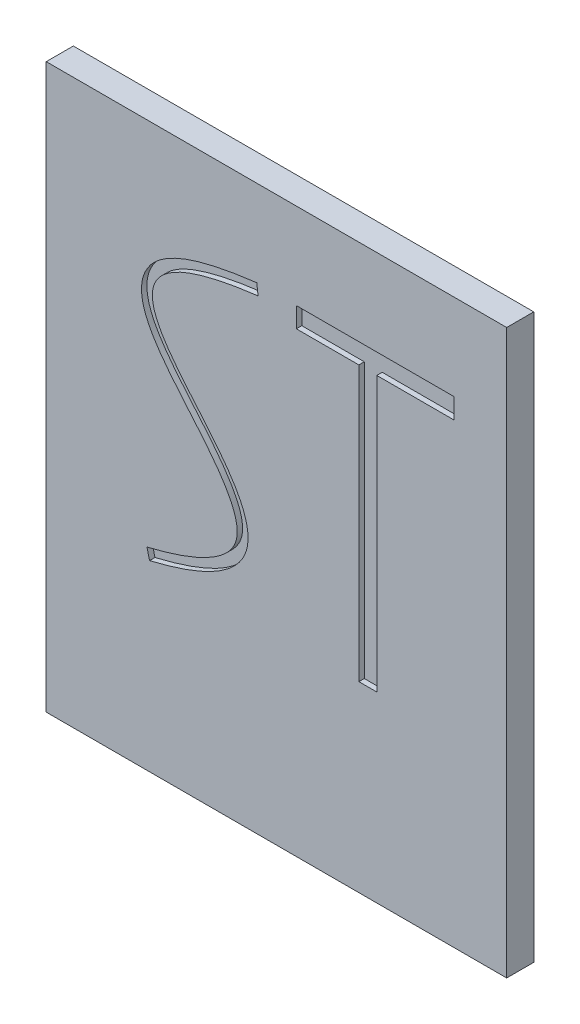
SolidWorks part; units mm, degrees
ref_plane "Front Plane" through (0, 0, 0) normal (0, 0, 1) x (1, 0, 0)
ref_plane "Top Plane" through (0, 0, 0) normal (0, 1, 0) x (1, 0, 0)
ref_plane "Right Plane" through (0, 0, 0) normal (1, 0, 0) x (0, 0, -1)
sketch "Esquisse1" plane through (0, 0, 0) normal (0, 0, 1) x (1, 0, 0)
  line L1 (42.5, 52) -> (-42.5, 52)
  line L2 (42.5, 52) -> (42.5, -52)
  line L3 (42.5, -52) -> (-42.5, -52)
  line L4 (-42.5, 52) -> (-42.5, -52)
  line L5 (42.5, 52) -> (-42.5, -52) construction
  line L6 (42.5, -52) -> (-42.5, 52) construction
  point P0 (0, 0)
  dimension "D1" = 85
  dimension "D2" = 104
extrude "Boss.-Extru.1" add sketch "Esquisse1" along normal blind 5
sketch "Esquisse2" plane through (0, 0, 5) normal (0, 0, 1) x (1, 0, 0)
  line L0 (-3.3887, 34.1033) -> (-3.6294, 36.0888)
  line L1 (-23.4325, -18.2413) -> (-23.8989, -16.2965)
  line L2 (3.6771, 36.0888) -> (32.8055, 36.0888)
  line L3 (32.8055, 36.0888) -> (32.8055, 32.3481)
  line L4 (32.8055, 32.3481) -> (18.5297, 32.3481)
  line L5 (18.5297, 32.3481) -> (18.5297, -18.2662)
  line L6 (18.5297, -18.2662) -> (15.2131, -18.2662)
  line L7 (15.2131, -18.2662) -> (15.2131, 32.3729)
  line L8 (15.2131, 32.3729) -> (3.6771, 32.3729)
  line L9 (3.6771, 32.3729) -> (3.6771, 36.0888)
  spline S0 degree 3 poles (-3.3887, 34.1033) (-33.854, 30.4105) (-10.8845, 9.3195) (2.0161, -12.1385) (-23.4325, -18.2413) knots 0 0 0 0 0.521999 1 1 1 1
  spline S1 degree 1 poles (-3.6294, 36.0888) (-23.8989, -16.2965) knots 0 0 1 1 construction
  spline S2 degree 3 poles (-3.6294, 36.0888) (-4.0845, 36.0337) (-5.0067, 35.9162) (-6.7465, 35.6715) (-8.7986, 35.3388) (-11.0513, 34.8996) (-13.7946, 34.2595) (-16.756, 33.3558) (-20.5885, 31.6726) (-23.2489, 29.5374) (-24.6679, 26.7862) (-25.0125, 24.5841) (-24.7507, 22.4318) (-23.8167, 19.6777) (-21.8456, 16.3581) (-18.7293, 12.3793) (-15.298, 8.3932) (-12.02, 4.4597) (-9.3049, 0.6584) (-7.548, -2.8726) (-7.1295, -5.3662) (-7.4109, -7.0994) (-7.9566, -8.3712) (-8.9456, -9.6902) (-10.5013, -11.0608) (-12.7101, -12.4436) (-15.1411, -13.5724) (-17.4624, -14.4465) (-19.3954, -15.0846) (-21.1751, -15.6008) (-22.6926, -16.0011) (-23.5002, -16.2008) (-23.8989, -16.2965) knots 0 0 0 0 0.007812 0.015625 0.03125 0.046875 0.0625 0.09375 0.125 0.1875 0.21875 0.25 0.28125 0.3125 0.375 0.4375 0.5 0.5625 0.625 0.6875 0.75 0.78125 0.8125 0.84375 0.875 0.90625 0.9375 0.953125 0.96875 0.984375 0.992188 1 1 1 1
  dimension "D1" = 2
extrude "Enlèv. mat.-Extru.1" cut sketch "Esquisse2" against normal blind 1
